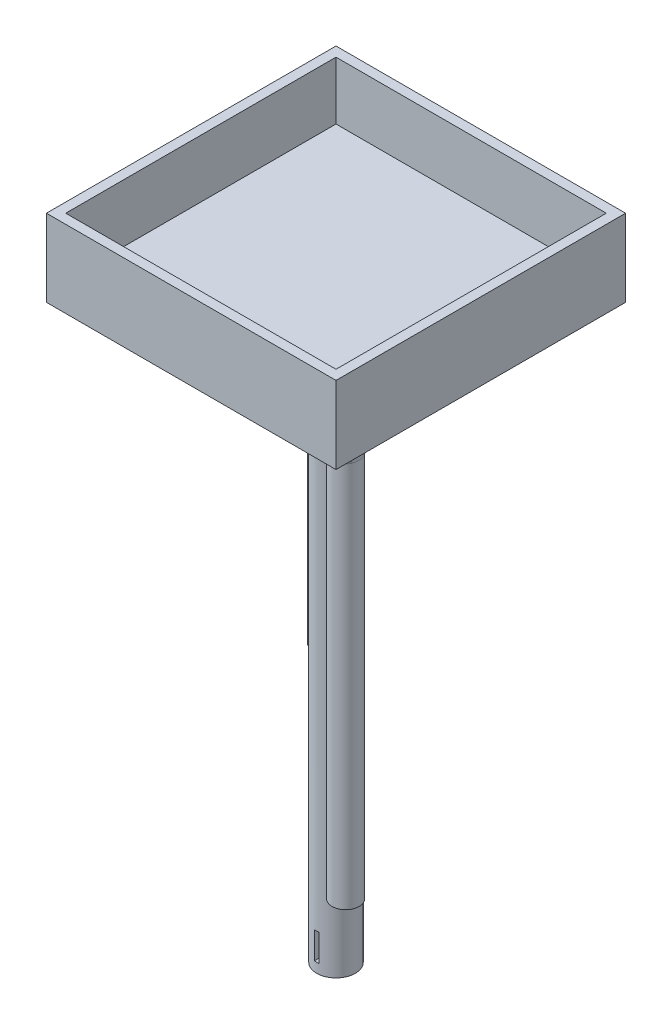
SolidWorks part; units mm, degrees
ref_plane "Plano frontal" through (0, 0, 0) normal (0, 0, 1) x (1, 0, 0)
ref_plane "Plano superior" through (0, 0, 0) normal (0, 1, 0) x (1, 0, 0)
ref_plane "Plano direito" through (0, 0, 0) normal (1, 0, 0) x (0, 0, -1)
sketch "Esboço1" plane through (0, 0, 0) normal (0, 1, 0) x (1, 0, 0)
  line L1 (-37.5, -37.5) -> (37.5, -37.5)
  line L2 (-37.5, -37.5) -> (-37.5, 37.5)
  line L3 (-37.5, 37.5) -> (37.5, 37.5)
  line L4 (37.5, -37.5) -> (37.5, 37.5)
  line L5 (-37.5, -37.5) -> (37.5, 37.5) construction
  line L6 (-37.5, 37.5) -> (37.5, -37.5) construction
  point P0 (0, 0)
  dimension "D1" = 75
  dimension "D2" = 75
extrude "Ressalto-extrusão1" add sketch "Esboço1" along normal blind 20
sketch "Esboço2" plane through (0, 20, 0) normal (0, 1, 0) x (1, 0, 0)
  line L1 (-35, -35) -> (35, -35)
  line L2 (-35, -35) -> (-35, 35)
  line L3 (-35, 35) -> (35, 35)
  line L4 (35, -35) -> (35, 35)
  line L5 (-35, -35) -> (35, 35) construction
  line L6 (-35, 35) -> (35, -35) construction
  point P0 (0, 0)
  dimension "D1" = 70
  dimension "D2" = 70
extrude "Corte-extrusão1" cut sketch "Esboço2" against normal blind 15
sketch "Esboço3" plane through (0, 0, 0) normal (0, -1, 0) x (-1, 0, 0)
  circle A0 centre (0, 0) radius 5
  dimension "D1" = 10
extrude "Ressalto-extrusão2" add sketch "Esboço3" along normal blind 148
sketch "Esboço5" plane through (0, 0, -37.5) normal (0, 0, -1) x (-1, 0, 0)
  line L0 (-37.5, 0) -> (37.5, 0) construction
  line L1 (0.6, -138.5) -> (-0.6, -138.5)
  line L2 (0.6, -138.5) -> (0.6, -145.5)
  line L3 (0.6, -145.5) -> (-0.6, -145.5)
  line L4 (-0.6, -138.5) -> (-0.6, -145.5)
  line L5 (0.6, -138.5) -> (-0.6, -145.5) construction
  line L6 (0.6, -145.5) -> (-0.6, -138.5) construction
  line L7 (37.5, 20) -> (37.5, 0) construction
  point P0 (0, -142)
  dimension "D1" = 7
  dimension "D2" = 1.2
  dimension "D3" = 142
  dimension "D4" = 37.5
extrude "Corte-extrusão2" cut sketch "Esboço5" against normal blind 70
sketch "Esboço7" plane through (0, 0, 0) normal (0, -1, 0) x (1, 0, 0)
  circle A0 centre (30, 27.5) radius 3.5
  circle A1 centre (-30, -27.5) radius 3.5
  dimension "D2" = 7
  dimension "D4" = 7
  dimension "D1" = 30
  dimension "D3" = 27.5
  dimension "D5" = 30
  dimension "D6" = 27.5
extrude "Ressalto-extrusão3" add sketch "Esboço7" along normal blind 105
fillet "Filete2" radius 5 1 edges at (-30, 0, -31)
fillet "Filete3" radius 5 1 edges at (30, 0, 24)
fillet "Filete4" radius 5 1 edges at (0, 0, -5)
